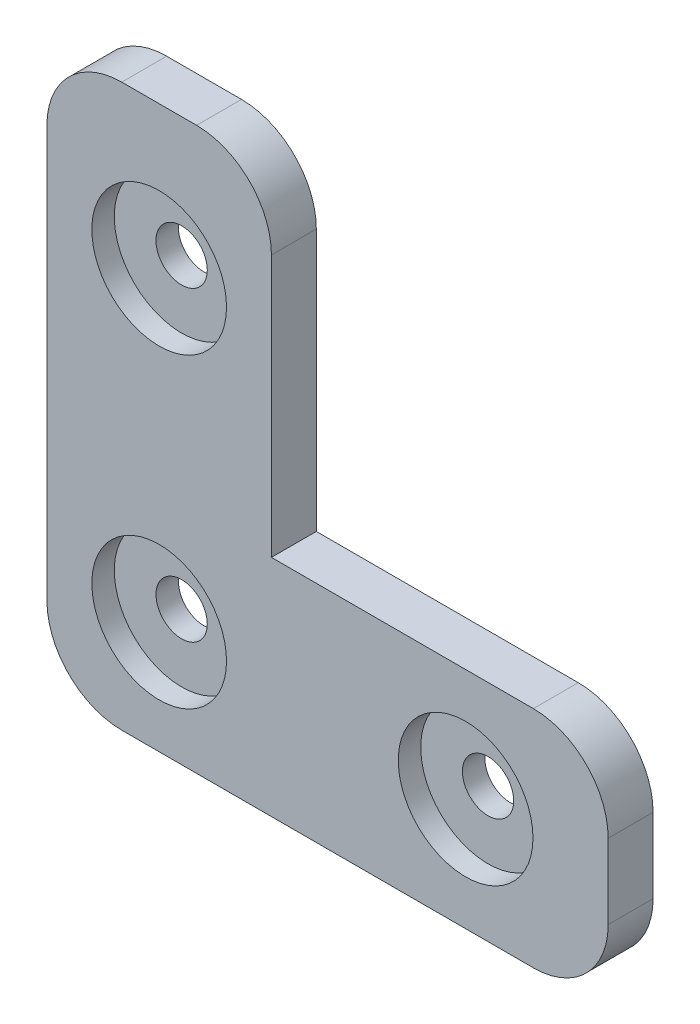
SolidWorks part; units mm, degrees
ref_plane "Front Plane" through (0, 0, 0) normal (0, 0, 1) x (1, 0, 0)
ref_plane "Top Plane" through (0, 0, 0) normal (0, 1, 0) x (1, 0, 0)
ref_plane "Right Plane" through (0, 0, 0) normal (1, 0, 0) x (0, 0, -1)
sketch "Sketch1" plane through (0, 0, 0) normal (0, 0, 1) x (1, 0, 0)
  line L0 (0, 0) -> (0, 75)
  line L1 (0, 75) -> (30, 75)
  line L2 (30, 75) -> (30, 30)
  line L3 (30, 30) -> (75, 30)
  line L4 (75, 30) -> (75, 0)
  line L5 (75, 0) -> (0, 0)
  dimension "D1" = 30
  dimension "D2" = 30
  dimension "D3" = 75
  dimension "D4" = 75
extrude "Boss-Extrude1" add sketch "Sketch1" along normal blind 6
sketch "Sketch2" plane through (0, 0, 6) normal (0, 0, 1) x (1, 0, 0)
  line L0 (15, 75) -> (15, 0) construction
  line L1 (30, 75) -> (0, 75) construction
  line L2 (0, 0) -> (75, 0) construction
  line L3 (75, 15) -> (0, 15) construction
  line L4 (75, 0) -> (75, 30) construction
  line L5 (0, 75) -> (0, 0) construction
  circle A0 centre (15, 15) radius 3.429
  circle A1 centre (15, 55.95) radius 3.429
  circle A2 centre (55.95, 15) radius 3.429
  dimension "D1" = 6.858
  dimension "D2" = 19.05
  dimension "D3" = 19.05
extrude "Cut-Extrude1" cut sketch "Sketch2" against normal through all
sketch "Sketch3" plane through (0, 0, 6) normal (0, 0, 1) x (1, 0, 0)
  circle A0 centre (55.95, 15) radius 9
  circle A1 centre (15, 15) radius 9
  circle A2 centre (15, 55.95) radius 9
  dimension "D1" = 18
extrude "Cut-Extrude2" cut sketch "Sketch3" against normal blind 3
fillet "Fillet1" radius 10 5 edges at (30, 75, 3) (0, 75, 3) (0, 0, 3) (75, 0, 3) (75, 30, 3)
